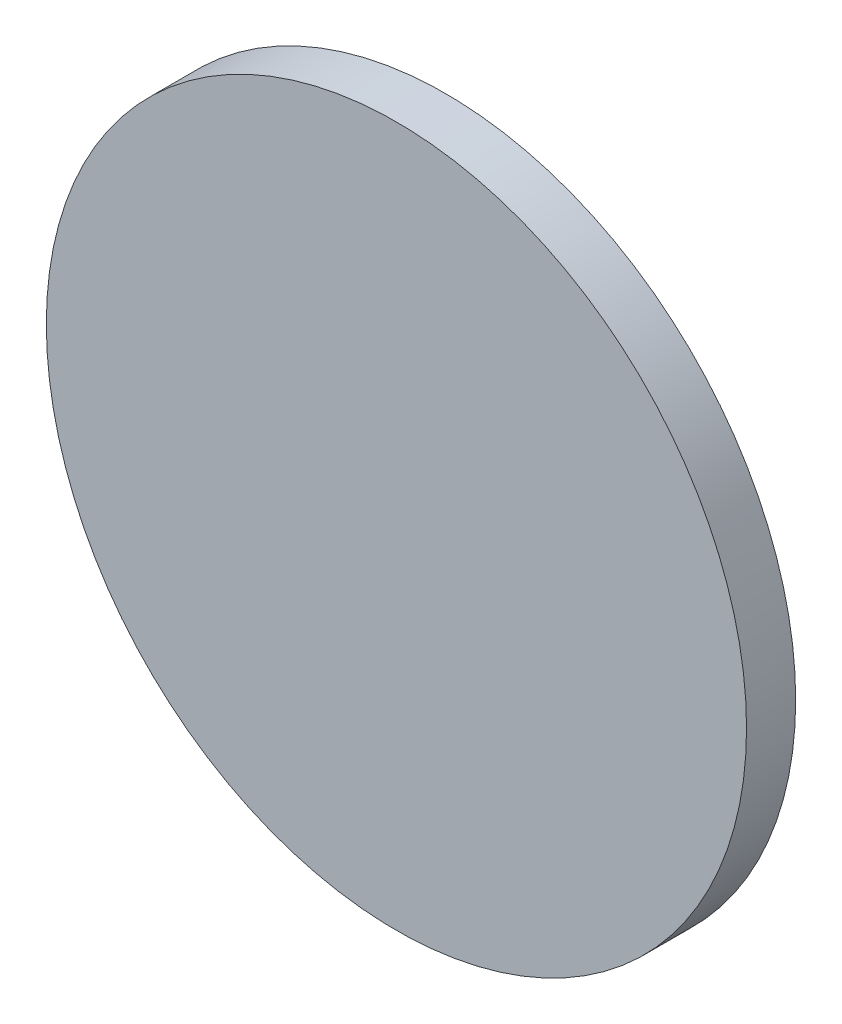
SolidWorks part; units mm, degrees
material "Vidrio"
ref_plane "Alzado" through (0, 0, 0) normal (0, 0, 1) x (1, 0, 0)
ref_plane "Planta" through (0, 0, 0) normal (0, 1, 0) x (1, 0, 0)
ref_plane "Vista lateral" through (0, 0, 0) normal (1, 0, 0) x (0, 0, -1)
sketch "Croquis1" plane through (0, 0, 0) normal (0, 0, 1) x (1, 0, 0)
  circle A0 centre (0, 0) radius 28.5
  dimension "D1" = 57
extrude "Saliente-Extruir1" add sketch "Croquis1" along normal blind 4
